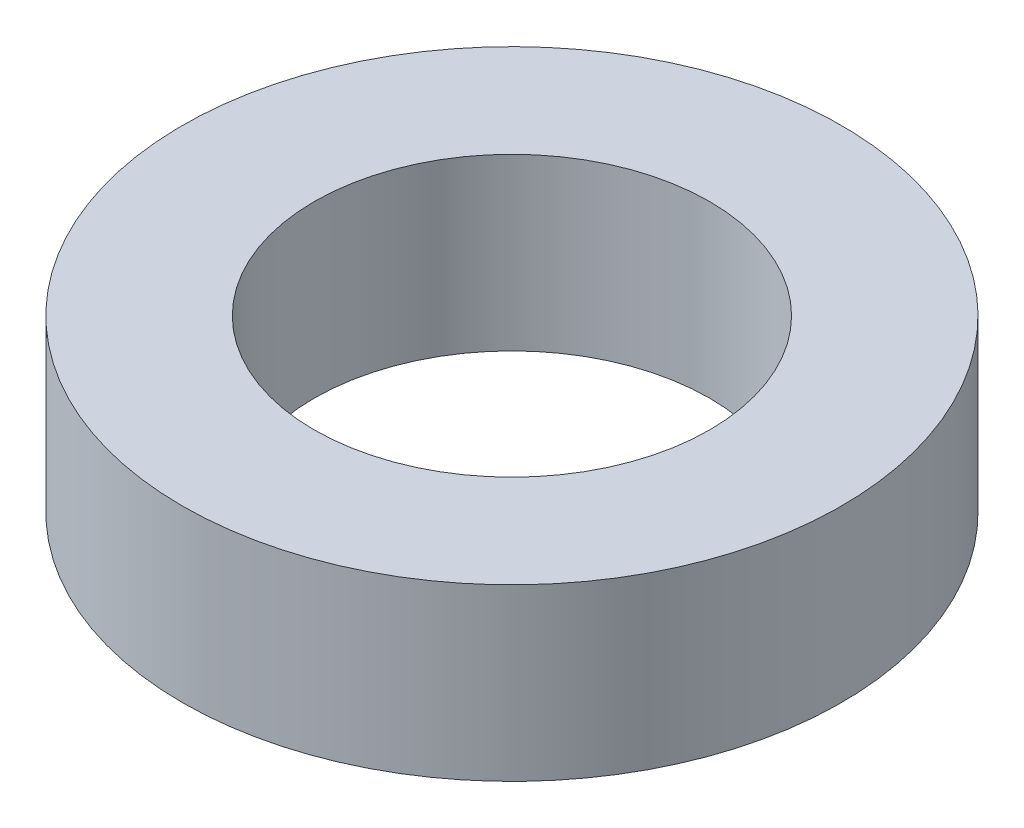
SolidWorks part; units mm, degrees
ref_plane "Front Plane" through (0, 0, 0) normal (0, 0, 1) x (1, 0, 0)
ref_plane "Top Plane" through (0, 0, 0) normal (0, 1, 0) x (1, 0, 0)
ref_plane "Right Plane" through (0, 0, 0) normal (1, 0, 0) x (0, 0, -1)
sketch "Sketch1" plane through (0, 0, 0) normal (0, 1, 0) x (1, 0, 0)
  circle A0 centre (0, 0) radius 9
  circle A1 centre (0, 0) radius 15
  dimension "D1" = 18
  dimension "D2" = 30
extrude "Boss-Extrude1" add sketch "Sketch1" along normal blind 7.75
